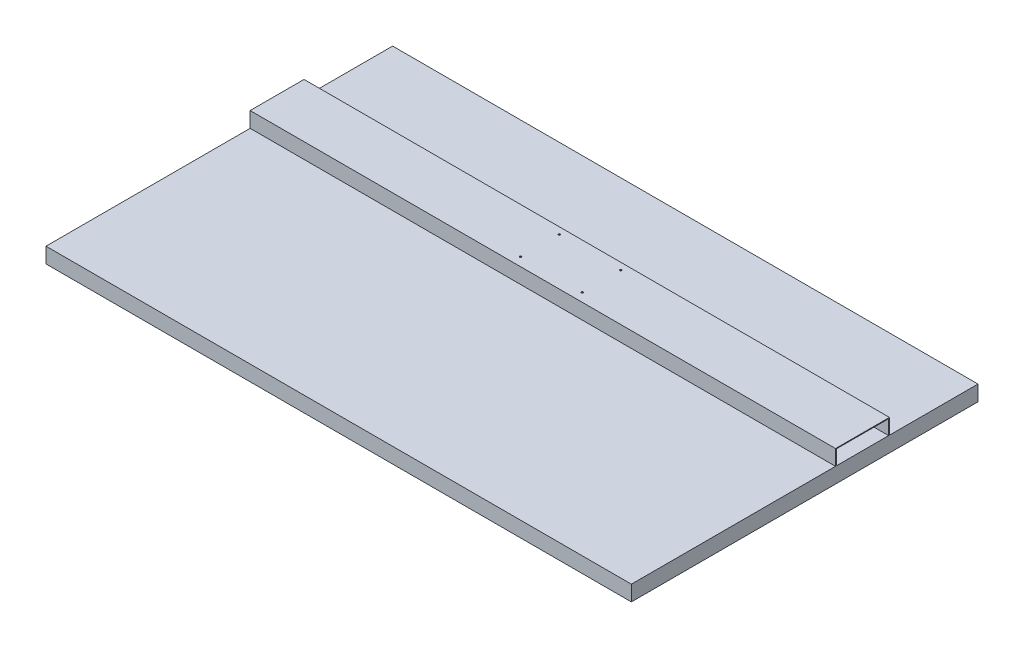
SolidWorks part; units mm, degrees
ref_plane "Front" through (0, 0, 0) normal (0, 0, 1) x (1, 0, 0)
ref_plane "Top" through (0, 0, 0) normal (0, 1, 0) x (1, 0, 0)
ref_plane "Right" through (0, 0, 0) normal (1, 0, 0) x (0, 0, -1)
sketch "Sketch1" plane through (0, 0, 0) normal (0, 1, 0) x (1, 0, 0)
  line L1 (-965.2, 571.5) -> (965.2, 571.5)
  line L2 (-965.2, 571.5) -> (-965.2, -571.5)
  line L3 (-965.2, -571.5) -> (965.2, -571.5)
  line L4 (965.2, 571.5) -> (965.2, -571.5)
  line L5 (-965.2, 571.5) -> (965.2, -571.5) construction
  line L6 (-965.2, -571.5) -> (965.2, 571.5) construction
  point P0 (0, 0)
  dimension "D1" = 1930.4
  dimension "D2" = 1143
extrude "Boss-Extrude1" add sketch "Sketch1" along normal blind 50.8
sketch "Sketch2" plane through (0, 0, 0) normal (0, 1, 0) x (1, 0, 0)
  line L1 (-930.8812, 534.8202) -> (930.8812, 534.8202)
  line L2 (-930.8812, 534.8202) -> (-930.8812, -534.8202)
  line L3 (-930.8812, -534.8202) -> (930.8812, -534.8202)
  line L4 (930.8812, 534.8202) -> (930.8812, -534.8202)
  line L5 (-930.8812, 534.8202) -> (930.8812, -534.8202) construction
  line L6 (-930.8812, -534.8202) -> (930.8812, 534.8202) construction
  point P0 (0, 0)
  dimension "D1" = 1861.7623
  dimension "D2" = 1069.6403
extrude "Cut-Extrude1" cut sketch "Sketch2" along normal blind 3.048
sketch "Sketch3" plane through (965.2, 0, 0) normal (1, 0, 0) x (0, 0, -1)
  line L0 (-571.5, 50.8) -> (571.5, 50.8) construction
  line L1 (101.6, 50.8) -> (104.14, 50.8)
  line L2 (101.6, 50.8) -> (101.6, 101.6)
  line L3 (101.6, 101.6) -> (279.4, 101.6)
  line L4 (279.4, 50.8) -> (279.4, 101.6)
  line L5 (276.86, 50.8) -> (279.4, 50.8)
  line L7 (104.14, 50.8) -> (104.14, 99.06)
  line L8 (104.14, 99.06) -> (276.86, 99.06)
  line L9 (276.86, 50.8) -> (276.86, 99.06)
  line L10 (571.5, 50.8) -> (571.5, 0) construction
  dimension "D1" = 2.54
  dimension "D2" = 2.54
  dimension "D3" = 292.1
  dimension "D4" = 177.8
  dimension "D5" = 50.8
extrude "Boss-Extrude3" add sketch "Sketch3" against normal through all
sketch "Sketch4" plane through (0, 101.6, 0) normal (0, 1, 0) x (1, 0, 0)
  line L0 (0, -571.5) -> (0, 571.5) construction
  line L1 (-965.2, -571.5) -> (965.2, -571.5) construction
  line L2 (965.2, 571.5) -> (-965.2, 571.5) construction
  line L4 (101.6, 257.175) -> (-101.6, 257.175) construction
  line L5 (101.6, 257.175) -> (101.6, 130.175) construction
  line L6 (101.6, 130.175) -> (-101.6, 130.175) construction
  line L7 (-101.6, 257.175) -> (-101.6, 130.175) construction
  line L8 (101.6, 257.175) -> (-101.6, 130.175) construction
  line L9 (101.6, 130.175) -> (-101.6, 257.175) construction
  circle A0 centre (101.6, 130.175) radius 3.175
  circle A1 centre (-101.6, 130.175) radius 3.175
  circle A2 centre (-101.6, 257.175) radius 3.175
  circle A3 centre (101.6, 257.175) radius 3.175
  point P6 (0, 193.675)
  dimension "D4" = 6.35
  dimension "D1" = 701.675
  dimension "D2" = 127
  dimension "D3" = 203.2
extrude "Cut-Extrude2" cut sketch "Sketch4" against normal up to next
